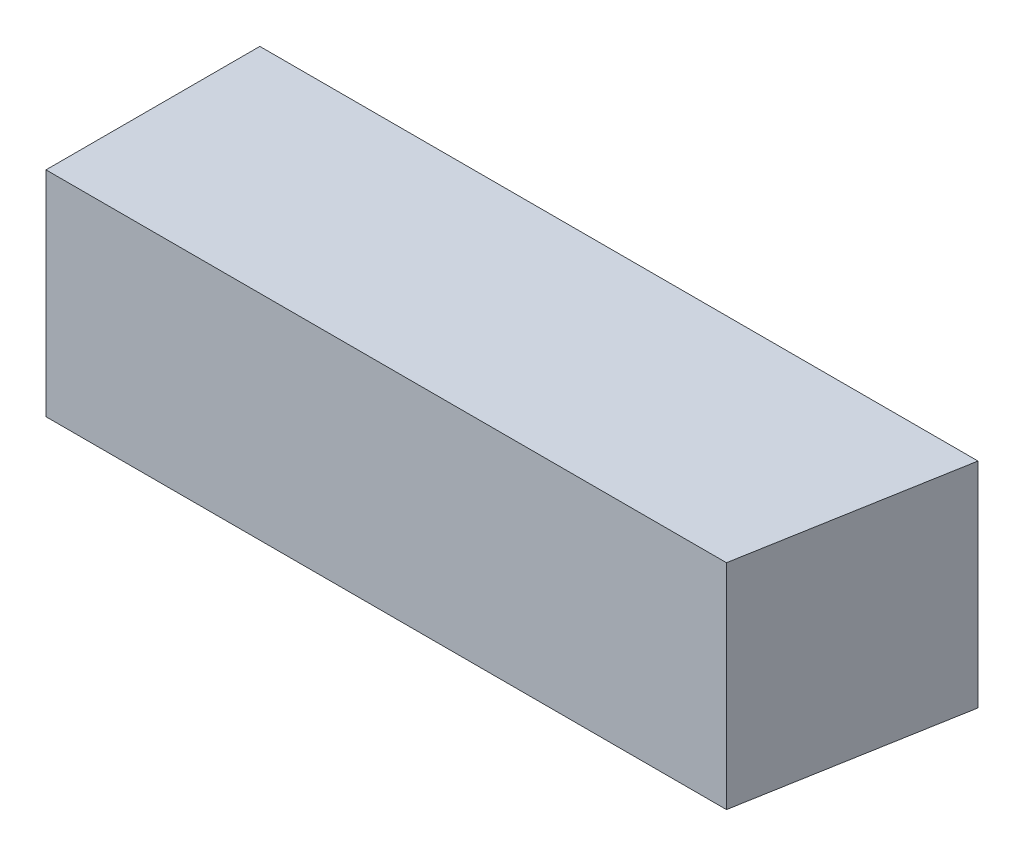
SolidWorks part; units mm, degrees
ref_plane "Front Plane" through (0, 0, 0) normal (1, 0, 0) x (0, 1, 0)
ref_plane "Top Plane" through (0, 0, 0) normal (0, 0, 1) x (0, 1, 0)
ref_plane "Right Plane" through (0, 0, 0) normal (0, 1, 0) x (-1, 0, 0)
sketch "Sketch1" plane through (0, 0, 0) normal (1, 0, 0) x (0, 1, 0)
  line L1 (0, 0) -> (88.9, 0)
  line L2 (0, 0) -> (0, 88.9)
  line L3 (0, 88.9) -> (88.9, 88.9)
  line L4 (88.9, 0) -> (88.9, 88.9)
  dimension "D1" = 88.9
  dimension "D2" = 88.9
extrude "Boss-Extrude1" add sketch "Sketch1" along normal blind 298.577
sketch "Sketch2" plane through (0, 0, 0) normal (0, 1, 0) x (-1, 0, 0)
  line L0 (-298.577, 0) -> (-282.9039, 88.9)
  line L1 (-298.577, 88.9) -> (0, 88.9) construction
  line L2 (-282.9039, 88.9) -> (-298.577, 88.9)
  line L3 (-298.577, 88.9) -> (-298.577, 0)
  dimension "D1" = 15.6731
extrude "Cut-Extrude1" cut sketch "Sketch2" along normal blind 88.9
